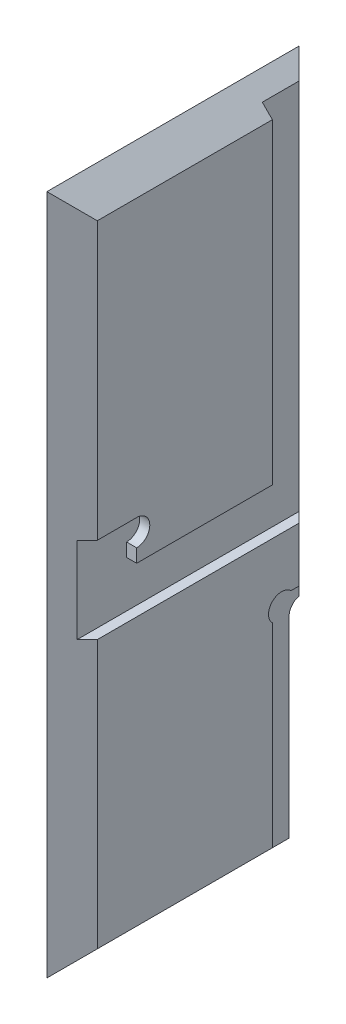
SolidWorks part; units mm, degrees
ref_plane "Front Plane" through (0, 0, 0) normal (0, 0, 1) x (1, 0, 0)
ref_plane "Top Plane" through (0, 0, 0) normal (0, 1, 0) x (1, 0, 0)
ref_plane "Right Plane" through (0, 0, 0) normal (1, 0, 0) x (0, 0, -1)
sketch "Sketch1" plane through (0, 0, 0) normal (1, 0, 0) x (0, 0, -1)
  line L1 (-63.5, 171.45) -> (63.5, 171.45)
  line L2 (-63.5, 171.45) -> (-63.5, -171.45)
  line L3 (-63.5, -171.45) -> (63.5, -171.45)
  line L4 (63.5, 171.45) -> (63.5, -171.45)
  line L8 (-63.5, 171.45) -> (63.5, -171.45) construction
  line L9 (-63.5, 171.45) -> (63.5, 171.45) construction
  line L10 (-63.5, 171.45) -> (-63.5, -171.45) construction
extrude "Boss-Extrude1" add sketch "Sketch1" along normal blind 12.7
draft "Draft1" type of draft neutral plane draft angle 45 faces to draft 4 face at (6.35, -171.45, 0) face at (6.35, 0, -63.5) face at (6.35, 0, 63.5) face at (6.35, 171.45, 0) neutral plane through (0, 0, 0) neutral plane normal (-1, 0, 0) reverse direction yes parameters "D1"=45
sketch "Sketch2" plane through (12.7, 0, 0) normal (1, 0, 0) x (0, 0, -1)
  line L0 (-63.5, 171.45) -> (-63.5, -171.45) construction
  line L1 (-63.5, 19.431) -> (-30.988, 19.431)
  line L2 (-63.5, 19.431) -> (-63.5, -23.876)
  line L4 (-30.988, 6.223) -> (-30.988, -0.508)
  line L5 (0, 0) -> (63.5, 0) construction
  line L6 (63.5, -171.45) -> (63.5, 171.45) construction
  line L7 (-63.5, -23.876) -> (63.5, -23.876)
  line L8 (63.5, -23.876) -> (63.5, -0.508)
  line L9 (63.5, -0.508) -> (-30.988, -0.508)
  line L10 (-50.419, 19.05) -> (-31.369, 19.05) construction
  line L11 (-31.369, -19.05) -> (-31.369, 19.05) construction
  arc A0 (-30.988, 19.431) -> (-30.988, 6.223) centre (-30.988, 12.827) cw
  dimension "D1" = 6.604
  dimension "D2" = 0.381
  dimension "D3" = 0.381
  dimension "D4" = 0.508
  dimension "D5" = 23.368
extrude "Cut-Extrude1" cut sketch "Sketch2" against normal blind 5.08 and the other way through all
sketch "Sketch3" plane through (12.7, 0, 0) normal (1, 0, 0) x (0, 0, -1)
  line L1 (37.338, -171.45) -> (63.5, -171.45)
  line L2 (37.338, -171.45) -> (37.338, -60.6475)
  line L3 (46.6775, -51.308) -> (63.5, -51.308)
  line L4 (63.5, -171.45) -> (63.5, -51.308)
  line L6 (37.719, -163.449) -> (37.719, -92.6847) construction
  line L7 (37.719, -51.689) -> (50.419, -51.689) construction
  line L8 (46.6775, -51.308) -> (37.338, -51.308) construction
  line L9 (37.338, -51.308) -> (37.338, -60.6475) construction
  arc A0 (46.6775, -51.308) -> (37.338, -60.6475) centre (42.0077, -55.9777) ccw
  dimension "D3" = 6.604
  dimension "D1" = 0.381
  dimension "D2" = 0.381
extrude "Cut-Extrude2" cut sketch "Sketch3" against normal blind 5.08
sketch "Sketch4" plane through (12.7, 0, 0) normal (1, 0, 0) x (0, 0, -1)
  line L1 (63.5, -171.45) -> (50.8, -171.45)
  line L2 (63.5, -171.45) -> (63.5, -60.579)
  line L3 (63.5, -60.579) -> (50.8, -60.579)
  line L4 (50.8, -171.45) -> (50.8, -60.579)
  line L5 (63.5, -60.579) -> (50.8, -60.579) construction
  line L6 (63.5, -171.45) -> (63.5, 171.45) construction
  line L7 (50.8, -51.308) -> (50.8, -23.876) construction
extrude "Cut-Extrude6" cut sketch "Sketch4" against normal through all
sketch "Sketch5" plane through (12.7, 0, 0) normal (1, 0, 0) x (0, 0, -1)
  line L0 (55.88, -0.508) -> (-30.988, -0.508) construction
  line L1 (63.5, 171.45) -> (37.338, 171.45)
  line L2 (63.5, 171.45) -> (63.5, -0.508)
  line L3 (63.5, -0.508) -> (37.338, -0.508)
  line L4 (37.338, 171.45) -> (37.338, -0.508)
  line L6 (37.719, 136.5082) -> (37.719, -17.0541) construction
  dimension "D1" = 0.381
extrude "Cut-Extrude7" cut sketch "Sketch5" against normal blind 5.08
fillet "Fillet1" radius 6.604 1 edges at (3.81, -60.579, -50.8)
